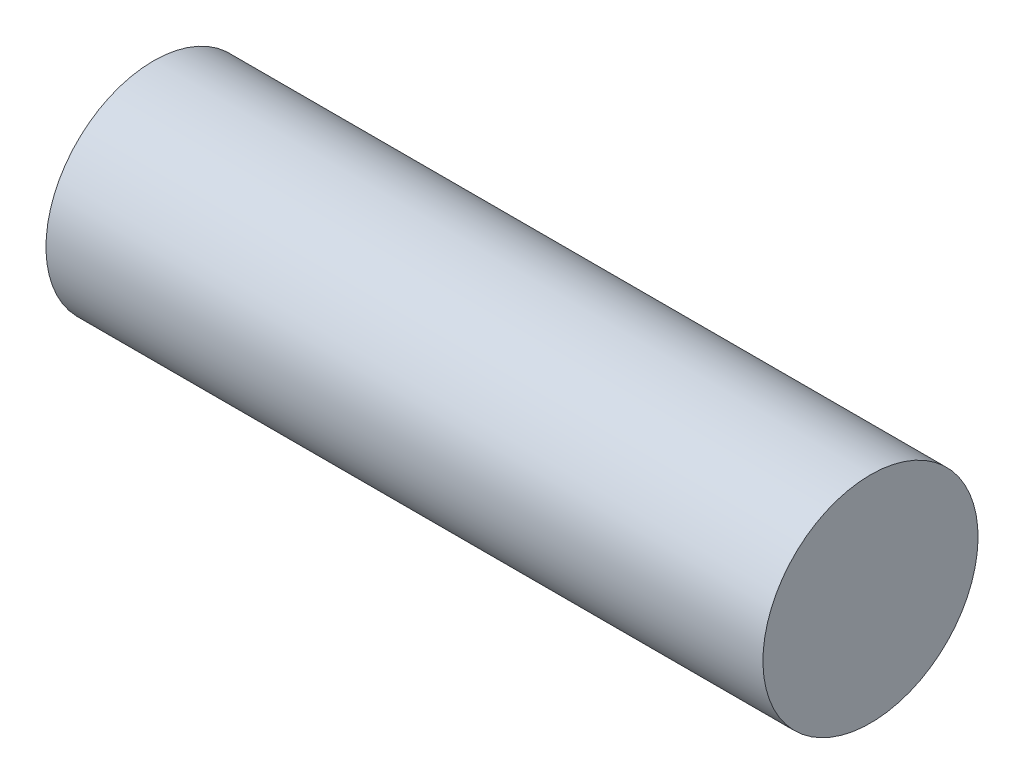
SolidWorks part; units mm, degrees
ref_plane "Front Plane" through (0, 0, 0) normal (0, 0, 1) x (1, 0, 0)
ref_plane "Top Plane" through (0, 0, 0) normal (0, 1, 0) x (1, 0, 0)
ref_plane "Right Plane" through (0, 0, 0) normal (1, 0, 0) x (0, 0, -1)
sketch "Sketch1" plane through (0, 0, 0) normal (0, 0, 1) x (1, 0, 0)
  line L0 (0, 0) -> (34.0278, 0.4159) construction
  line L1 (79.2658, 15.4159) -> (-20.7342, 15.4159)
  line L2 (79.2658, 15.4159) -> (79.2658, 0.4159)
  line L3 (79.2658, 0.4159) -> (-20.7342, 0.4159)
  line L4 (-20.7342, 15.4159) -> (-20.7342, 0.4159)
  dimension "D1" = 15
  dimension "D2" = 100
revolve "Revolve1" add sketch "Sketch1" angle 360 about L3
